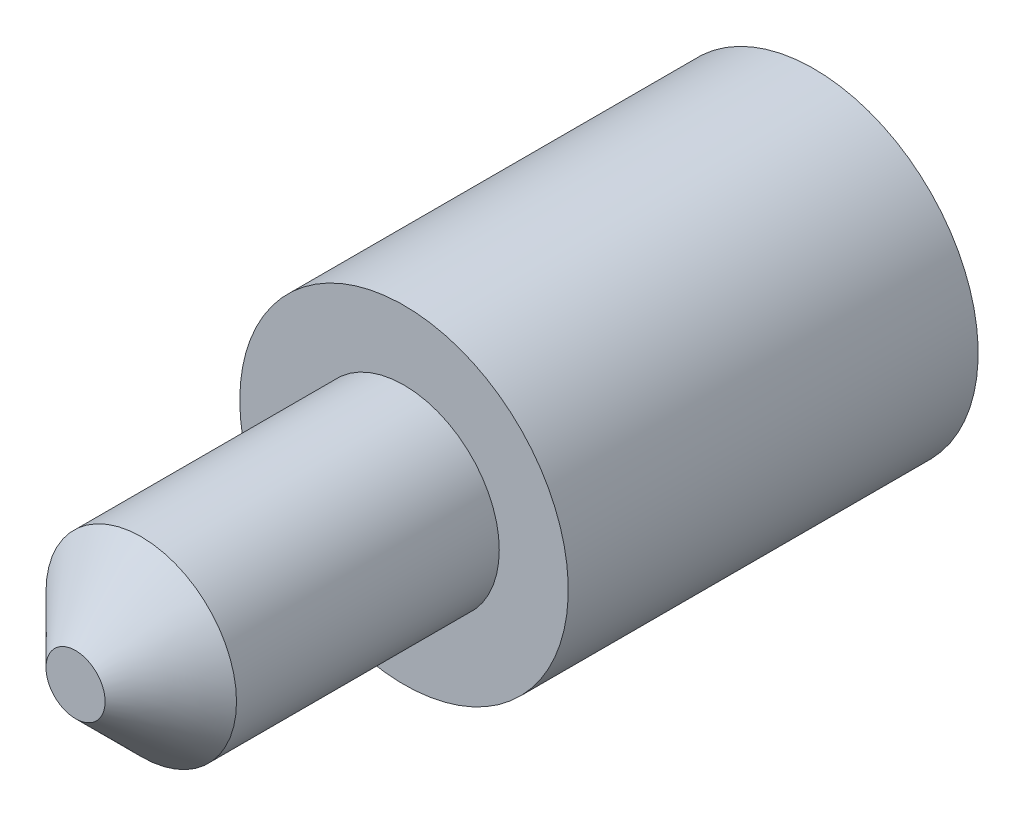
SolidWorks part; units mm, degrees
material "Латунь"
ref_plane "Спереди" through (0, 0, 0) normal (0, 0, 1) x (1, 0, 0)
ref_plane "Сверху" through (0, 0, 0) normal (0, 1, 0) x (1, 0, 0)
ref_plane "Справа" through (0, 0, 0) normal (1, 0, 0) x (0, 0, -1)
sketch "Эскиз1" plane through (0, 0, 0) normal (0, 0, 1) x (1, 0, 0)
  circle A0 centre (0, 0) radius 2.5
  dimension "D1" = 5
extrude "Бобышка-Вытянуть1" add sketch "Эскиз1" along normal blind 6.24
sketch "Эскиз2" plane through (0, 0, 6.24) normal (0, 0, 1) x (1, 0, 0)
  circle A0 centre (0, 0) radius 1.45
  dimension "D1" = 2.9
extrude "Бобышка-Вытянуть2" add sketch "Эскиз2" along normal blind 5
hole_wizard "Отверстие обработанное метчиком M3x0.51" positions "Эскиз4" profile "Эскиз3" tap size "M3x0.5" standard "Ansi Metric"
sketch "Эскиз4" plane through (0, 0, 0) normal (0, 0, -1) x (-1, 0, 0)
  point P0 (0, 0)
sketch "Эскиз3" plane through (0, 0, 0) normal (1, 0, 0) x (0, 1, 0)
  line L0 (0, 0) -> (0, 5.7511)
  line L1 (0, 5.7511) -> (1.25, 5)
  line L2 (1.25, 5) -> (1.25, 0)
  line L5 (1.25, 0) -> (0, 0)
  line L10 (0, 5.7511) -> (-1.25, 5) construction
  line L11 (0, -6.35) -> (0, 107.95) construction
  dimension "Диаметр сверла" = 2.5
  dimension "Глубина сверла" = 5
  dimension "Угол заточки сверла" = 118
cosmetic thread "Отверстие резьбы1" parameters "D1"=5, "D2"=3
chamfer "Фаска1" distance 1 angle 45 1 edges at (1.45, 0, 11.24)
